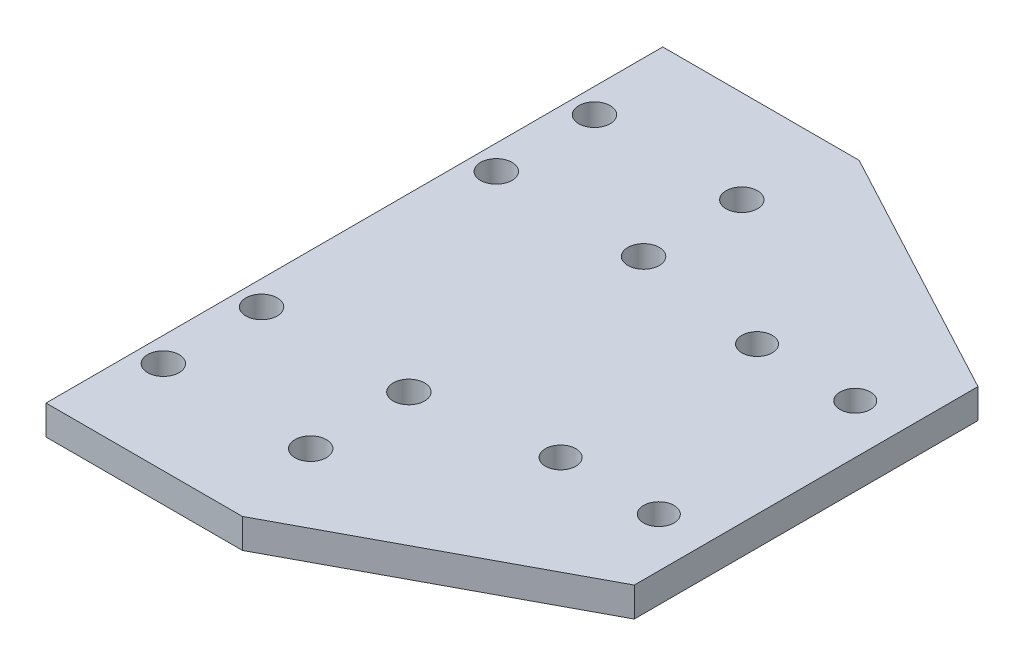
SolidWorks part; units mm, degrees
ref_plane "前视基准面" through (0, 0, 0) normal (0, 0, 1) x (1, 0, 0)
ref_plane "上视基准面" through (0, 0, 0) normal (0, 1, 0) x (1, 0, 0)
ref_plane "右视基准面" through (0, 0, 0) normal (1, 0, 0) x (0, 0, -1)
other "Configuration Table"
sketch "草图1" plane through (0, 0, 0) normal (0, 1, 0) x (1, 0, 0)
  line L0 (-50, 0) -> (73, 0) construction
  line L2 (-50, -31.4) -> (-50, 31.4)
  line L5 (-50, 31.4) -> (-30, 31.4)
  line L6 (-4, 17.5) -> (-4, -17.5)
  line L7 (-50, 31.4) -> (-30, 31.4) construction
  line L8 (-50, 31.4) -> (-50, -31.4) construction
  line L9 (-50, -31.4) -> (-30, -31.4) construction
  line L10 (-30, 31.4) -> (-30, -31.4) construction
  line L11 (-40, 31.4) -> (-40, -31.4) construction
  line L12 (-47.5, 21.95) -> (-47.5, 11.95) construction
  line L13 (-47.5, 11.95) -> (-47.5, 15.6052)
  line L14 (-47.5, 16.95) -> (-40, 16.95) construction
  line L15 (-47.5, -16.95) -> (-40, -16.95) construction
  line L16 (-47.5, -21.95) -> (-47.5, -11.95) construction
  line L17 (-47.5, -11.95) -> (-47.5, -15.6052)
  line L18 (-4, -17.5) -> (-30, -31.4)
  line L19 (-30, 31.4) -> (-4, 17.5)
  line L20 (-50, -31.4) -> (-30, -31.4)
  line L21 (-19, 10) -> (-9, 10) construction
  line L22 (-19, -10) -> (-9, -10) construction
  line L23 (-14, 10) -> (-14, -10) construction
  circle A0 centre (-47.5, 21.95) radius 1.6
  circle A1 centre (-32.5, 21.95) radius 1.6
  circle A2 centre (-47.5, 11.95) radius 1.6
  circle A3 centre (-32.5, 11.95) radius 1.6
  circle A4 centre (-32.5, -11.95) radius 1.6
  circle A5 centre (-47.5, -11.95) radius 1.6
  circle A6 centre (-32.5, -21.95) radius 1.6
  circle A7 centre (-47.5, -21.95) radius 1.6
  circle A8 centre (-19, 10) radius 1.55
  circle A9 centre (-9, 10) radius 1.55
  circle A10 centre (-9, -10) radius 1.55
  circle A11 centre (-19, -10) radius 1.55
  point P0 (0, 0)
  dimension "D5" = 3.2
  dimension "D10" = 3.1
  dimension "D11" = 3.1
  dimension "D2" = 62.8
  dimension "D3" = 20
  dimension "D4" = 10
  dimension "D6" = 10
  dimension "D7" = 15
  dimension "D8" = 33.9
  dimension "D9" = 10
  dimension "D12" = 10
  dimension "D13" = 10
  dimension "D14" = 26
  dimension "D15" = 35
extrude "凸台-拉伸1" add sketch "草图1" along normal blind 3
